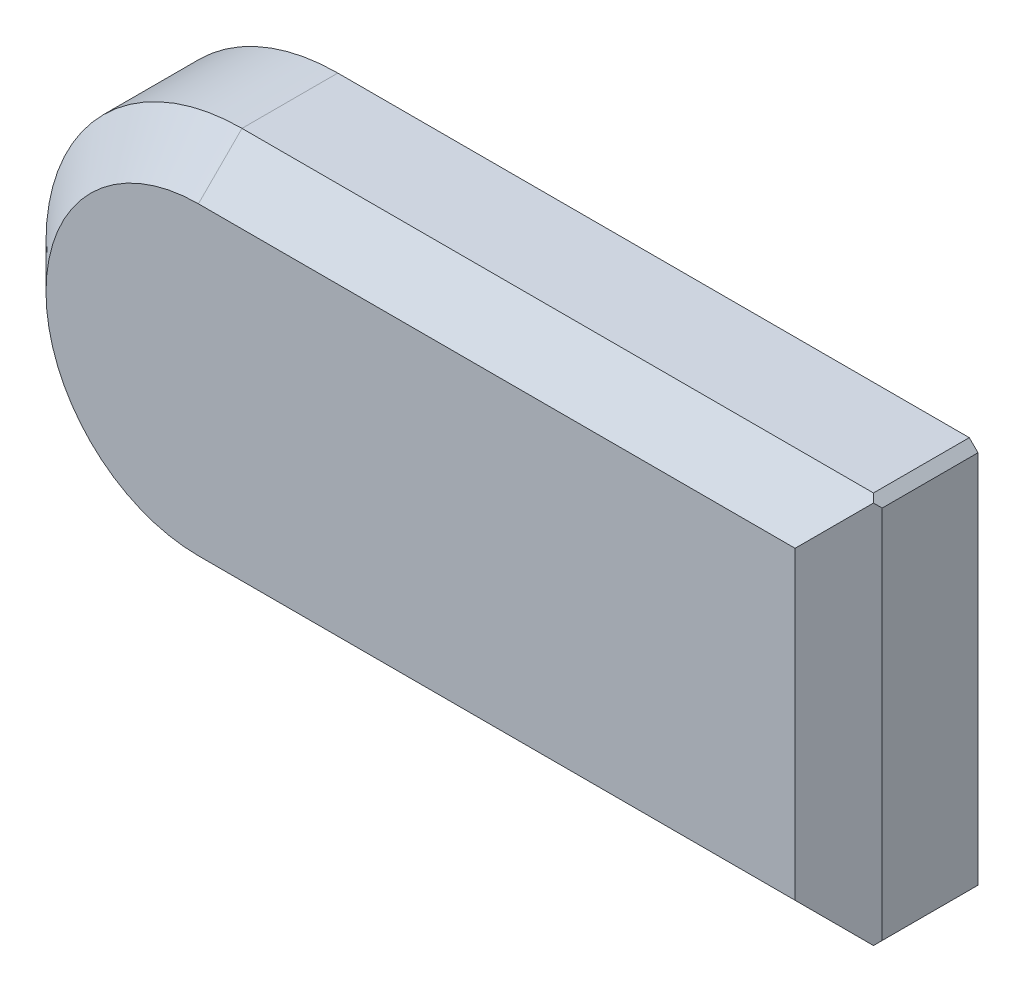
SolidWorks part; units mm, degrees
ref_plane "前视基准面" through (0, 0, 0) normal (0, 0, 1) x (1, 0, 0)
ref_plane "上视基准面" through (0, 0, 0) normal (0, 1, 0) x (1, 0, 0)
ref_plane "右视基准面" through (0, 0, 0) normal (1, 0, 0) x (0, 0, -1)
other "Configuration Table"
sketch "草图1" plane through (0, 0, 0) normal (0, 0, 1) x (1, 0, 0)
  line L1 (-36.75, 22.5) -> (36.75, 22.5)
  line L2 (-36.75, 22.5) -> (-36.75, -22.5)
  line L3 (-36.75, -22.5) -> (36.75, -22.5)
  line L4 (36.75, 22.5) -> (36.75, -22.5)
  line L5 (-36.75, 22.5) -> (36.75, -22.5) construction
  line L6 (-36.75, -22.5) -> (36.75, 22.5) construction
  circle A0 centre (-36.75, 0) radius 22.5
  point P0 (0, 0)
  dimension "D1" = 73.5
  dimension "D2" = 45
extrude "凸台-拉伸1" add sketch "草图1" along normal blind 16 contours L2 A0 | L2 A0 | A0 L3 L4 L1
chamfer "倒角1" distance 5 angle 45 4 edges at (0, -22.5, 16) (-59.25, 0, 16) (0, 22.5, 16) (36.75, 0, 16)
shell "抽壳1" thickness 2.5
sketch "草图2" plane through (0, 0, 0) normal (0, 0, -1) x (-1, 0, 0)
  line L0 (36.75, -20) -> (-34.25, -20) construction
  line L1 (36.75, 20) -> (-34.25, 20) construction
  line L2 (-34.25, 20) -> (-34.25, -20) construction
  line L3 (36.75, -20) -> (-34.25, -20)
  line L4 (36.75, 20) -> (-34.25, 20)
  line L5 (-34.25, 20) -> (-34.25, -20)
  line L6 (36.75, 21.2) -> (-35.45, 21.2)
  line L7 (-35.45, 21.2) -> (-35.45, -21.2)
  line L8 (36.75, -21.2) -> (-35.45, -21.2)
  arc A0 (36.75, -20) -> (36.75, 20) centre (36.75, 0) ccw construction
  arc A1 (36.75, -20) -> (36.75, 20) centre (36.75, 0) ccw
  arc A2 (36.75, -21.2) -> (36.75, 21.2) centre (36.75, 0) ccw
  dimension "D1" = 1.2
extrude "切除-拉伸1" cut sketch "草图2" against normal blind 1.2
sketch "草图3" plane through (0, 0, 13.5) normal (0, 0, -1) x (-1, 0, 0)
  line L0 (-36.75, 0) -> (11.25, 0) construction
  line L1 (-36.75, 22.5) -> (-36.75, -22.5) construction
  circle A0 centre (11.25, 0) radius 5
  dimension "D2" = 10
  dimension "D1" = 48
extrude "凸台-拉伸2" add sketch "草图3" along normal offset from surface (12.5 mm away) 1 up to face at (-5.95, 0, 0)
sketch "草图4" plane through (0, 0, 1) normal (0, 0, -1) x (-1, 0, 0)
  line L1 (9.6623, -2.75) -> (12.8377, -2.75)
  line L2 (12.8377, -2.75) -> (14.4254, 0)
  line L3 (14.4254, 0) -> (12.8377, 2.75)
  line L4 (12.8377, 2.75) -> (9.6623, 2.75)
  line L5 (9.6623, 2.75) -> (8.0746, 0)
  line L6 (8.0746, 0) -> (9.6623, -2.75)
  circle A0 centre (11.25, 0) radius 2.75 construction
  dimension "D1" = 5.5
extrude "切除-拉伸2" cut sketch "草图4" against normal blind 2.4
sketch "草图5" plane through (0, 0, 3.4) normal (0, 0, -1) x (-1, 0, 0)
  circle A0 centre (11.25, 0) radius 1.6
  dimension "D1" = 3.2
extrude "切除-拉伸3" cut sketch "草图5" against normal blind 6
chamfer "倒角2" distance 1 angle 45 2 edges at (36.75, 22.5, 5.5) (36.75, -22.5, 5.5)
